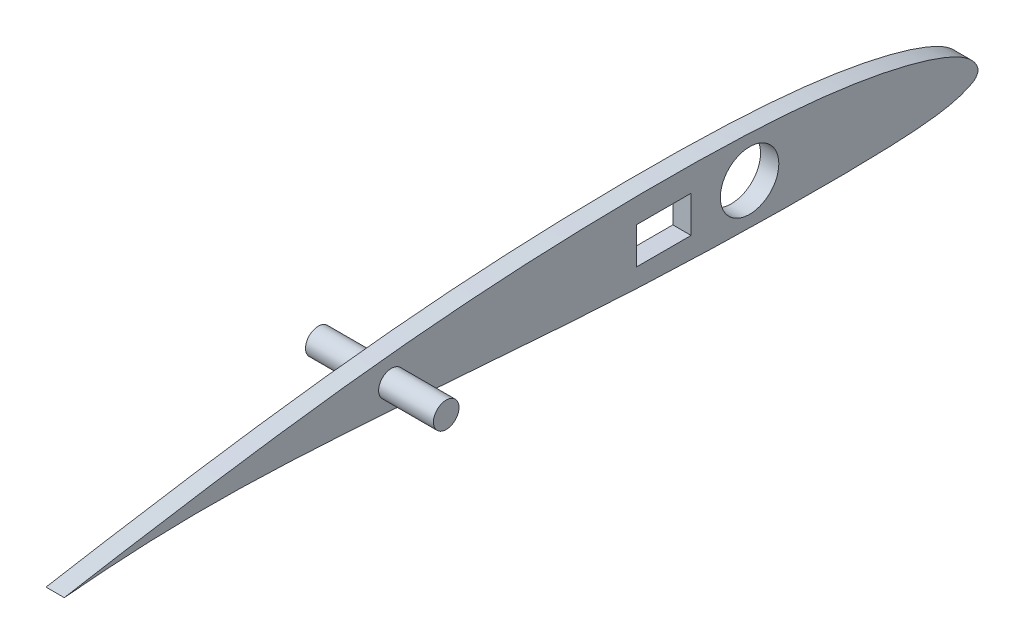
SolidWorks part; units mm, degrees
material "ABS generico"
ref_plane "Piano frontale" through (0, 0, 0) normal (0, 0, 1) x (1, 0, 0)
ref_plane "Piano superiore" through (0, 0, 0) normal (0, 1, 0) x (1, 0, 0)
ref_plane "Piano destro" through (0, 0, 0) normal (1, 0, 0) x (0, 0, -1)
curve "Curva1"
  spline degree 3 poles (0, 0.1724, 248.285) (0, -0.053, 250.4273) (0, 0.2462, 248.3284) (0, 0.5529, 246.6445) (0, 1.2459, 242.6221) (0, 2.0989, 237.7464) (0, 3.1818, 231.3634) (0, 4.2933, 223.9772) (0, 5.7312, 215.5604) (0, 7.1315, 206.3004) (0, 8.6324, 196.1631) (0, 10.1162, 185.3524) (0, 11.5493, 173.9891) (0, 12.8816, 162.1914) (0, 14.0593, 150.0724) (0, 15.0523, 137.7438) (0, 15.8256, 125.3116) (0, 16.3834, 112.8888) (0, 16.7267, 100.597) (0, 16.8648, 88.5669) (0, 16.792, 76.9314) (0, 16.4941, 65.8165) (0, 15.9609, 55.3329) (0, 15.1594, 45.573) (0, 14.0978, 36.6074) (0, 12.7884, 28.4972) (0, 11.2839, 21.2988) (0, 9.6413, 15.0749) (0, 7.9136, 9.8809) (0, 6.1182, 5.7699) (0, 4.2384, 2.7289) (0, 2.3057, 0.8126) (0, 0.7927, 0.0312) (0, -0.4105, -0.0213) (0, -1.7115, 0.4949) (0, -2.8658, 2.6253) (0, -4.0404, 5.6977) (0, -4.9287, 10.0719) (0, -5.5974, 15.6262) (0, -6.0122, 22.4122) (0, -6.265, 30.3619) (0, -6.3814, 39.3972) (0, -6.3554, 49.3987) (0, -6.2185, 60.2453) (0, -5.9476, 71.8018) (0, -5.5368, 83.9408) (0, -4.9386, 96.5461) (0, -4.1527, 109.5201) (0, -3.2196, 122.7671) (0, -2.1909, 136.1764) (0, -1.148, 149.6158) (0, -0.1602, 162.9314) (0, 0.706, 175.9537) (0, 1.3896, 188.4999) (0, 1.8332, 200.3712) (0, 1.9676, 211.3376) (0, 1.8232, 221.1842) (0, 1.4973, 229.6804) (0, 1.0741, 236.8065) (0, 0.6857, 242.1894) (0, 0.3087, 246.5181) (0, 0.1724, 248.285) (0, -0.053, 250.4273) (0, 0.2462, 248.3284) knots -0.014202 -0.006329 -0.001589 0 0.001576 0.006211 0.01368 0.023764 0.036307 0.051658 0.068045 0.086769 0.107053 0.128647 0.151303 0.174786 0.19886 0.223309 0.247929 0.272522 0.296848 0.320648 0.343669 0.365658 0.3864 0.405741 0.423561 0.439779 0.454311 0.467034 0.477831 0.486643 0.493542 0.498786 0.50271 0.50309 0.505896 0.510322 0.516831 0.525521 0.536535 0.549945 0.565696 0.583577 0.603379 0.624844 0.647727 0.671743 0.696673 0.722357 0.748609 0.77521 0.801891 0.828329 0.854175 0.879074 0.902636 0.924421 0.943939 0.960827 0.974827 0.985798 0.993671 0.998411 1 1.001576 1.006211 1.01368 periodic
sketch "Schizzo1" plane through (0, 0, 0) normal (1, 0, 0) x (0, 0, -1)
  line L0 (-250, 0) -> (0.0001, 0.0174) construction
  line L1 (0.0001, 0.0174) -> (-0.0034, 50.0174) construction
  line L2 (-62.4999, 16.3096) -> (-62.4999, -6.155) construction
  line L4 (-78.4999, 10.0773) -> (-93.4999, 10.0773)
  line L5 (-78.4999, 10.0773) -> (-78.4999, 0.0773)
  line L6 (-78.4999, 0.0773) -> (-93.4999, 0.0773)
  line L7 (-93.4999, 10.0773) -> (-93.4999, 0.0773)
  circle A0 centre (-62.4999, 5.0773) radius 8
  spline S0 degree 3 poles (-248.3284, 0.2462) (-250.4273, -0.053) (-248.285, 0.1724) (-246.5181, 0.3087) (-242.1894, 0.6857) (-236.8065, 1.0741) (-229.6804, 1.4973) (-221.1842, 1.8232) (-211.3376, 1.9676) (-200.3712, 1.8332) (-188.4999, 1.3896) (-175.9537, 0.706) (-162.9314, -0.1602) (-149.6158, -1.148) (-136.1764, -2.1909) (-122.7671, -3.2196) (-109.5201, -4.1527) (-96.5461, -4.9386) (-83.9408, -5.5368) (-71.8018, -5.9476) (-60.2453, -6.2185) (-49.3987, -6.3554) (-39.3972, -6.3814) (-30.3619, -6.265) (-22.4122, -6.0122) (-15.6262, -5.5974) (-10.0719, -4.9287) (-5.6977, -4.0404) (-2.6253, -2.8658) (-0.4949, -1.7115) (0.0213, -0.4105) (-0.0312, 0.7927) (-0.8126, 2.3057) (-2.7289, 4.2384) (-5.7699, 6.1182) (-9.8809, 7.9136) (-15.0749, 9.6413) (-21.2988, 11.2839) (-28.4972, 12.7884) (-36.6074, 14.0978) (-45.573, 15.1594) (-55.3329, 15.9609) (-65.8165, 16.4941) (-76.9314, 16.792) (-88.5669, 16.8648) (-100.597, 16.7267) (-112.8888, 16.3834) (-125.3116, 15.8256) (-137.7438, 15.0523) (-150.0724, 14.0593) (-162.1914, 12.8816) (-173.9891, 11.5493) (-185.3524, 10.1162) (-196.1631, 8.6324) (-206.3004, 7.1315) (-215.5604, 5.7312) (-223.9772, 4.2933) (-231.3634, 3.1818) (-237.7464, 2.0989) (-242.6221, 1.2459) (-246.6445, 0.5529) (-248.3284, 0.2462) (-250.4273, -0.053) (-248.285, 0.1724) knots -0.01368 -0.006211 -0.001576 0 0.001589 0.006329 0.014202 0.025173 0.039173 0.056061 0.075579 0.097364 0.120926 0.145825 0.171671 0.198109 0.22479 0.251391 0.277643 0.303327 0.328257 0.352273 0.375156 0.396621 0.416423 0.434304 0.450055 0.463465 0.474479 0.483169 0.489678 0.494104 0.49691 0.49729 0.501214 0.506458 0.513357 0.522169 0.532966 0.545689 0.560221 0.576439 0.594259 0.6136 0.634342 0.656331 0.679352 0.703152 0.727478 0.752071 0.776691 0.80114 0.825214 0.848697 0.871353 0.892947 0.913231 0.931955 0.948342 0.963693 0.976236 0.98632 0.993789 0.998424 1 1.001589 1.006329 1.014202 only from (-250, 0) to (-250, 0) construction
  spline S1 degree 3 poles (-248.3284, 0.2462) (-250.4273, -0.053) (-248.285, 0.1724) (-246.5181, 0.3087) (-242.1894, 0.6857) (-236.8065, 1.0741) (-229.6804, 1.4973) (-221.1842, 1.8232) (-211.3376, 1.9676) (-200.3712, 1.8332) (-188.4999, 1.3896) (-175.9537, 0.706) (-162.9314, -0.1602) (-149.6158, -1.148) (-136.1764, -2.1909) (-122.7671, -3.2196) (-109.5201, -4.1527) (-96.5461, -4.9386) (-83.9408, -5.5368) (-71.8018, -5.9476) (-60.2453, -6.2185) (-49.3987, -6.3554) (-39.3972, -6.3814) (-30.3619, -6.265) (-22.4122, -6.0122) (-15.6262, -5.5974) (-10.0719, -4.9287) (-5.6977, -4.0404) (-2.6253, -2.8658) (-0.4949, -1.7115) (0.0213, -0.4105) (-0.0312, 0.7927) (-0.8126, 2.3057) (-2.7289, 4.2384) (-5.7699, 6.1182) (-9.8809, 7.9136) (-15.0749, 9.6413) (-21.2988, 11.2839) (-28.4972, 12.7884) (-36.6074, 14.0978) (-45.573, 15.1594) (-55.3329, 15.9609) (-65.8165, 16.4941) (-76.9314, 16.792) (-88.5669, 16.8648) (-100.597, 16.7267) (-112.8888, 16.3834) (-125.3116, 15.8256) (-137.7438, 15.0523) (-150.0724, 14.0593) (-162.1914, 12.8816) (-173.9891, 11.5493) (-185.3524, 10.1162) (-196.1631, 8.6324) (-206.3004, 7.1315) (-215.5604, 5.7312) (-223.9772, 4.2933) (-231.3634, 3.1818) (-237.7464, 2.0989) (-242.6221, 1.2459) (-246.6445, 0.5529) (-248.3284, 0.2462) (-250.4273, -0.053) (-248.285, 0.1724) knots -0.01368 -0.006211 -0.001576 0 0.001589 0.006329 0.014202 0.025173 0.039173 0.056061 0.075579 0.097364 0.120926 0.145825 0.171671 0.198109 0.22479 0.251391 0.277643 0.303327 0.328257 0.352273 0.375156 0.396621 0.416423 0.434304 0.450055 0.463465 0.474479 0.483169 0.489678 0.494104 0.49691 0.49729 0.501214 0.506458 0.513357 0.522169 0.532966 0.545689 0.560221 0.576439 0.594259 0.6136 0.634342 0.656331 0.679352 0.703152 0.727478 0.752071 0.776691 0.80114 0.825214 0.848697 0.871353 0.892947 0.913231 0.931955 0.948342 0.963693 0.976236 0.98632 0.993789 0.998424 1 1.001589 1.006329 1.014202 only from (-250, 0) to (-250, 0)
  point P11 (-78.4999, 5.0773)
  dimension "D3" = 16
  dimension "D1" = 50
  dimension "D2" = 62.5
  dimension "D4" = 15
  dimension "D5" = 10
  dimension "D6" = 16
extrude "CorpoFoam" add sketch "Schizzo1" along normal blind 5
sketch "Schizzo2" plane through (0, 0, 0) normal (-1, 0, 0) x (0, 0, 1)
  circle A0 centre (160.4999, 6.0773) radius 3.5
  circle A1 centre (62.4999, 5.0773) radius 8 construction
  dimension "D1" = 7
  dimension "D2" = 98
  dimension "D3" = 1
extrude "PernoAggancio" add sketch "Schizzo2" along normal blind 15 and the other way blind 20
